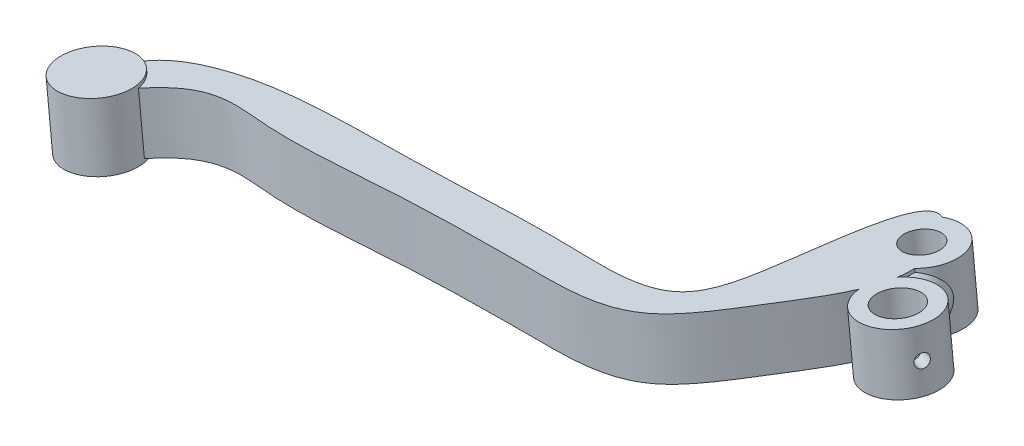
SolidWorks part; units mm, degrees
material "Aleación 6061"
ref_plane "Alzado" through (0, 0, 0) normal (0, 0, 1) x (1, 0, 0)
ref_plane "Planta" through (0, 0, 0) normal (0, 1, 0) x (1, 0, 0)
ref_plane "Vista lateral" through (0, 0, 0) normal (1, 0, 0) x (0, 0, -1)
sketch3d "Sk_puntos_Plano_palanca"
  point P0 (247.8038, 40.2316, -26.1614)
  point P1 (297.3062, 35.1814, -31.0616)
  point P2 (252.6788, 39.7343, 23.5979)
ref_plane "Plano_palanca" through (6.6148, 64.8378, 0) normal (-0.1015, -0.9948, 0) x (-0.9948, 0.1015, 0)
sketch "Sk_Palanca" plane through (6.6148, 64.8378, 0) normal (-0.1015, -0.9948, 0) x (-0.9948, 0.1015, 0)
  spline S0 degree 3 poles (-254.9118, 3.3768) (-241.8709, -13.9666) (-252.1672, -26.5391) (-262.1509, -40.9172) (-282.5977, -38.6131) (-302.0678, -36.9124) (-321.774, -36.7308) (-335.8922, -32.7728) (-346.4274, -47.4224) (-345.1262, -34.2001) (-335.6003, -29.8606) (-321.0748, -29.329) (-301.3541, -31.6126) (-282.7257, -32.1429) (-261.0715, -35.6467) (-257.2358, -19.9312) (-254.9118, 3.3768) (-241.8709, -13.9666) (-252.1672, -26.5391) knots -0.158059 -0.111967 -0.033021 0 0.078946 0.135623 0.200779 0.301384 0.381877 0.43514 0.476712 0.500852 0.542424 0.595686 0.67618 0.776785 0.841941 0.888033 0.966979 1 1.078946 1.135623 1.200779 only from (-246.2677, -9.6359) to (-246.2677, -9.6359)
extrude "Palanca" add sketch "Sk_Palanca" along normal mid plane 9
sketch3d "Sk_Buje_pivote"
  line L0 (253.8287, 35.0936, 8.3663) -> (254.7422, 44.0471, 8.3663)
  dimension "D1" = 9
sweep "Buje_pivote" add path "Sk_Buje_pivote" circular profile diameter 11 parameters "D3"=11
sketch3d "Sk_Bola"
  line L0 (349.3548, 24.8454, 40.1035) -> (350.3697, 34.7938, 40.1035)
  dimension "D1" = 10
sweep "Bola" add path "Sk_Bola" circular profile diameter 11 parameters "D3"=11
sketch3d "Sk_Brazo_cabezal"
  line L0 (254.2854, 39.5704, 8.3663) -> (247.241, 40.289, 19.112)
  dimension "D1" = 12.869
sweep "Brazo_cabezal" add path "Sk_Brazo_cabezal" circular profile diameter 8 parameters "D3"=8
sketch3d "Sk_Oreja_cabezal"
  line L0 (246.7843, 35.8123, 19.112) -> (247.6978, 44.7658, 19.112)
  dimension "D1" = 9
sweep "Oreja_cabezal" add path "Sk_Oreja_cabezal" circular profile diameter 11 parameters "D3"=11
sketch3d "Sk_Agujero_pivote"
  line L0 (253.4735, 31.6117, 8.3663) -> (255.0974, 47.5291, 8.3663)
  dimension "D1" = 16
sweep "Agujero_pivote" cut path "Sk_Agujero_pivote" circular profile diameter 5.5 parameters "D3"=5.5
sketch3d "Sk_Alojamiento_cabezal"
  line L0 (246.6321, 34.32, 19.112) -> (247.85, 46.2581, 19.112)
  dimension "D1" = 12
sweep "Alojamiento_cabezal" cut path "Sk_Alojamiento_cabezal" circular profile diameter 6.5 parameters "D3"=6.5
sketch3d "Sk_Salida_cable"
  line L0 (247.241, 40.289, 19.112) -> (238.5451, 41.1762, 22.1835)
  dimension "D1" = 9.265
sweep "Salida_cable" cut path "Sk_Salida_cable" circular profile diameter 2 parameters "D3"=2
mirror "Simetria_lado_izq" about plane through (0, 0, 0) normal (1, 0, 0) of bodies 108
delete or keep bodies "Borrar_original_dcho" type delete bodies bodies 108
